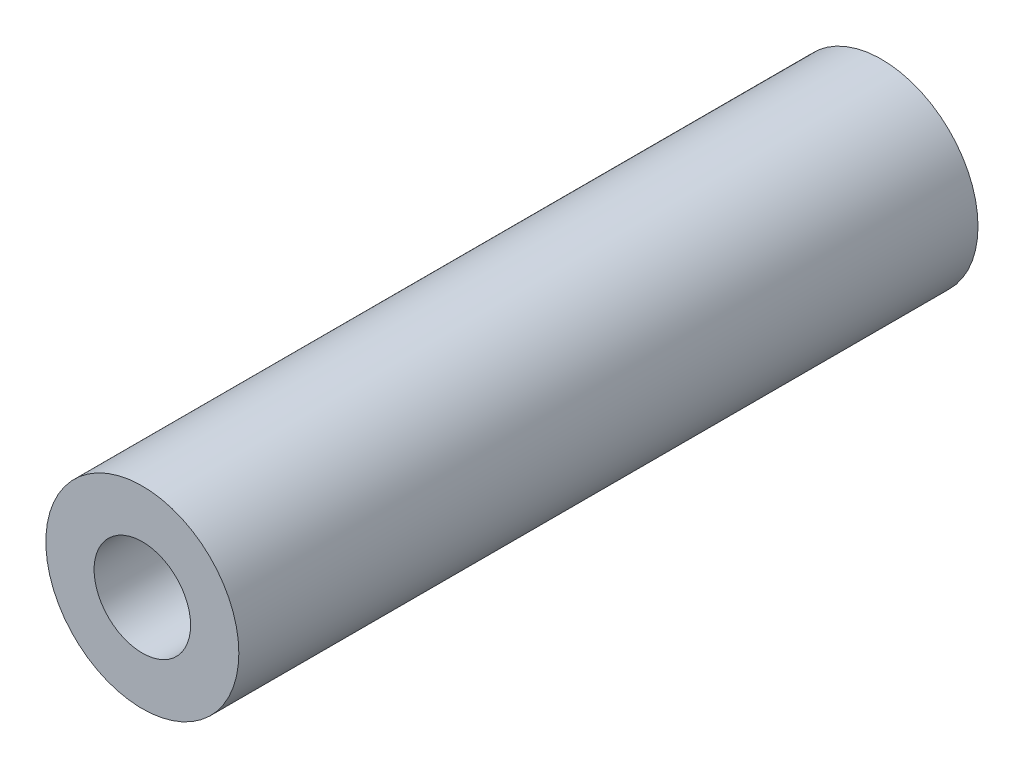
SolidWorks part; units mm, degrees
material "6061-T6 (SS)"
ref_plane "Front Plane" through (0, 0, 0) normal (0, 0, 1) x (1, 0, 0)
ref_plane "Top Plane" through (0, 0, 0) normal (0, 1, 0) x (1, 0, 0)
ref_plane "Right Plane" through (0, 0, 0) normal (1, 0, 0) x (0, 0, -1)
sketch "Sketch1" plane through (0, 0, 0) normal (0, 0, 1) x (1, 0, 0)
  circle A0 centre (0, 0) radius 2.5
  dimension "D1" = 5
extrude "Boss-Extrude1" add sketch "Sketch1" along normal mid plane 19.15 contours A0
hole_wizard "M3x0.5 Tapped Hole1" positions "3DSketch1" profile "Sketch2" tap size "M3x0.5" standard "ANSI Metric"
sketch3d "3DSketch1"
  line L0 (0, 0, 9.575) -> (0, 0, -9.575) construction
  point P0 (0, 0, 9.575)
sketch "Sketch2" plane through (0, 0, 9.575) normal (1, 0, 0) x (0, -1, 0)
  line L0 (0, 0) -> (0, 10.3261)
  line L1 (0, 10.3261) -> (1.25, 9.575)
  line L2 (1.25, 9.575) -> (1.25, 0)
  line L5 (1.25, 0) -> (0, 0)
  line L10 (0, 10.3261) -> (-1.25, 9.575) construction
  line L11 (0, -6.35) -> (0, 107.95) construction
  dimension "Tap Drill Dia." = 2.5
  dimension "Tap Drill Depth" = 9.575
  dimension "Drill Angle" = 118
cosmetic thread "Hole Thread1" parameters "D1"=6, "D2"=3
mirror "Mirror1" about plane through (0, 0, 0) normal (0, 0, 1) of "M3x0.5 Tapped Hole1"
cosmetic thread "Hole Thread2" parameters "D1"=6, "D2"=3
